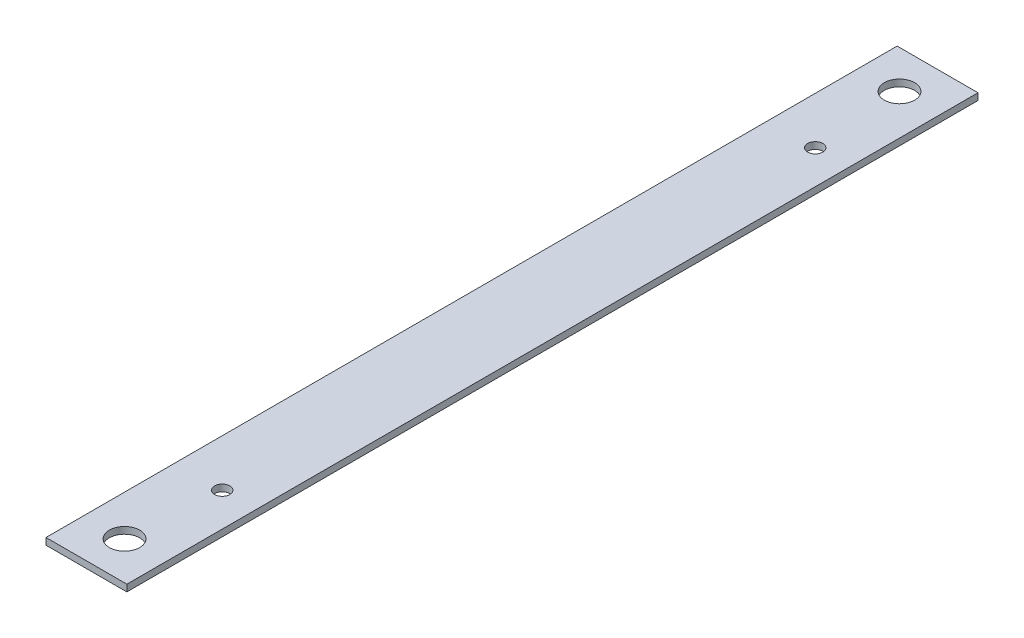
SolidWorks part; units mm, degrees
material "Plain Carbon Steel"
ref_plane "Front Plane" through (0, 0, 0) normal (0, 0, 1) x (1, 0, 0)
ref_plane "Top Plane" through (0, 0, 0) normal (0, 1, 0) x (1, 0, 0)
ref_plane "Right Plane" through (0, 0, 0) normal (1, 0, 0) x (0, 0, -1)
sketch "Sketch1" plane through (0, 0, 0) normal (0, 0, 1) x (1, 0, 0)
  line L1 (0, 0) -> (38.1, 0)
  line L2 (0, 0) -> (0, 3.175)
  line L3 (0, 3.175) -> (38.1, 3.175)
  line L4 (38.1, 0) -> (38.1, 3.175)
  dimension "D1" = 38.1
  dimension "D2" = 3.175
extrude "Boss-Extrude1" add sketch "Sketch1" along normal blind 401.0152
sketch "Sketch2" plane through (0, 3.175, 0) normal (0, 1, 0) x (1, 0, 0)
  line L0 (19.05, -383.0701) -> (19.05, -401.0152) construction
  line L1 (19.05, -17.9451) -> (19.05, -383.0701) construction
  line L2 (38.1, -401.0152) -> (0, -401.0152) construction
  line L3 (38.1, 0) -> (0, 0) construction
  line L4 (19.05, 0) -> (19.05, -144.6164) construction
  line L5 (38.1, -200.5076) -> (0, -200.5076) construction
  line L6 (38.1, -401.0152) -> (38.1, 0) construction
  line L7 (0, -401.0152) -> (0, 0) construction
  line L8 (19.05, -200.5076) -> (19.05, -257.6576) construction
  line L9 (19.05, -200.5076) -> (19.05, -143.3576) construction
  line L10 (19.05, -200.5076) -> (19.05, -60.8076) construction
  line L11 (19.05, -60.8076) -> (22.225, -60.8076) construction
  circle A0 centre (19.05, -383.0701) radius 7.1438
  circle A1 centre (19.05, -17.9451) radius 7.1438
  circle A2 centre (22.225, -60.8076) radius 3.556
  circle A3 centre (22.225, -340.2076) radius 3.556
  point P4 (19.05, -200.5076)
  point P11 (19.05, -144.6164)
  point P13 (19.05, -340.2076)
  point P14 (19.05, -60.8076)
  point P23 (19.05, -251.3076)
  dimension "D2" = 139.7
  dimension "D1" = 365.125
  dimension "D3" = 139.7
extrude "Cut-Extrude1" cut sketch "Sketch2" against normal through all
